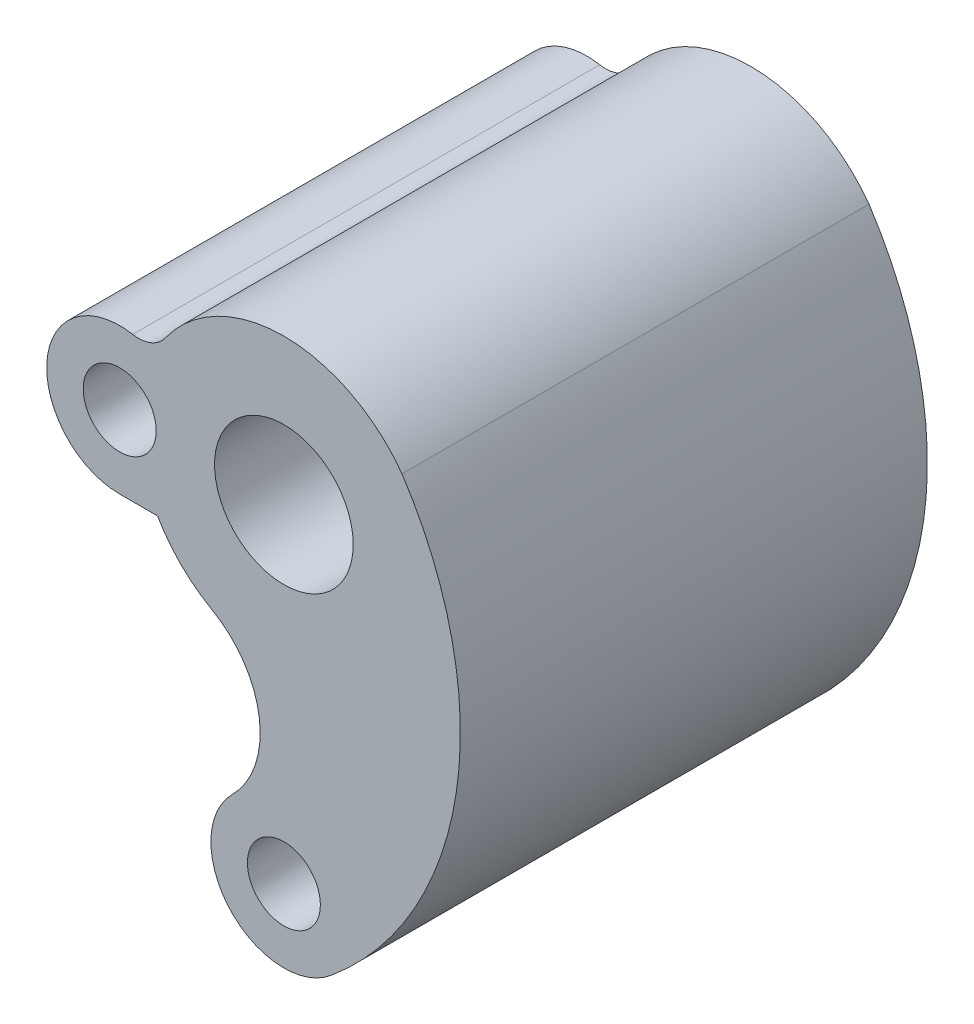
SolidWorks part; units mm, degrees
ref_plane "Front Plane" through (0, 0, 0) normal (0, 0, 1) x (1, 0, 0)
ref_plane "Top Plane" through (0, 0, 0) normal (0, 1, 0) x (1, 0, 0)
ref_plane "Right Plane" through (0, 0, 0) normal (1, 0, 0) x (0, 0, -1)
sketch "Sketch1" plane through (0, 0, 0) normal (0, 0, 1) x (1, 0, 0)
  line L0 (0, 0) -> (-159.4332, 0) construction
  line L1 (-159.4332, 0) -> (113.107, 0) construction
  line L2 (-56.8331, 48.9845) -> (-56.8331, -65.5933) construction
  line L3 (-11.8331, 48.9845) -> (-11.8331, -122.7487) construction
  line L4 (-159.4332, -90) -> (118.0084, -90) construction
  line L5 (-74.7216, -8.9443) -> (-29.7216, -98.9443)
  line L6 (-56.8331, -20) -> (-46.4741, -20)
  circle A0 centre (-56.8331, 0) radius 10
  arc A1 (-53.2699, 19.68) -> (-56.8331, -20) centre (-56.8331, 0) ccw
  circle A2 centre (-11.8331, -90) radius 10
  arc A3 (-25.9628, -75.8454) -> (1.3156, -105.0702) centre (-11.8331, -90) ccw
  circle A4 centre (-11.8331, 0) radius 14
  circle A5 centre (-11.8331, 0) radius 19
  arc A6 (-46.4741, -20) -> (-31.529, -34.8148) centre (-11.8331, 0) ccw
  arc A7 (-25.9628, -75.8454) -> (-31.529, -34.8148) centre (-44.3313, -57.4444) ccw
  arc A8 (20.5421, 23.4914) -> (-44.3501, 23.2947) centre (-11.8331, 0) ccw
  arc A9 (1.3156, -105.0702) -> (20.5421, 23.4914) centre (-61.0417, -30.0262) ccw
  arc A10 (-44.3501, 23.2947) -> (-53.2699, 19.68) centre (-51.6664, 28.536) cw
  point P30 (-11.8288, -122.7487)
  point P31 (-56.8331, -65.5933)
  dimension "D3" = 20
  dimension "D4" = 40
  dimension "D5" = 20
  dimension "D6" = 40
  dimension "D7" = 28
  dimension "D8" = 38
  dimension "D9" = 80
  dimension "D10" = 52
  dimension "D11" = 9
  dimension "D1" = 90
  dimension "D2" = 45
extrude "Boss-Extrude1" add sketch "Sketch1" along normal blind 128 contours A8 A10 A1 L6 A6 A7 A3 A9 A0 A2 A5
